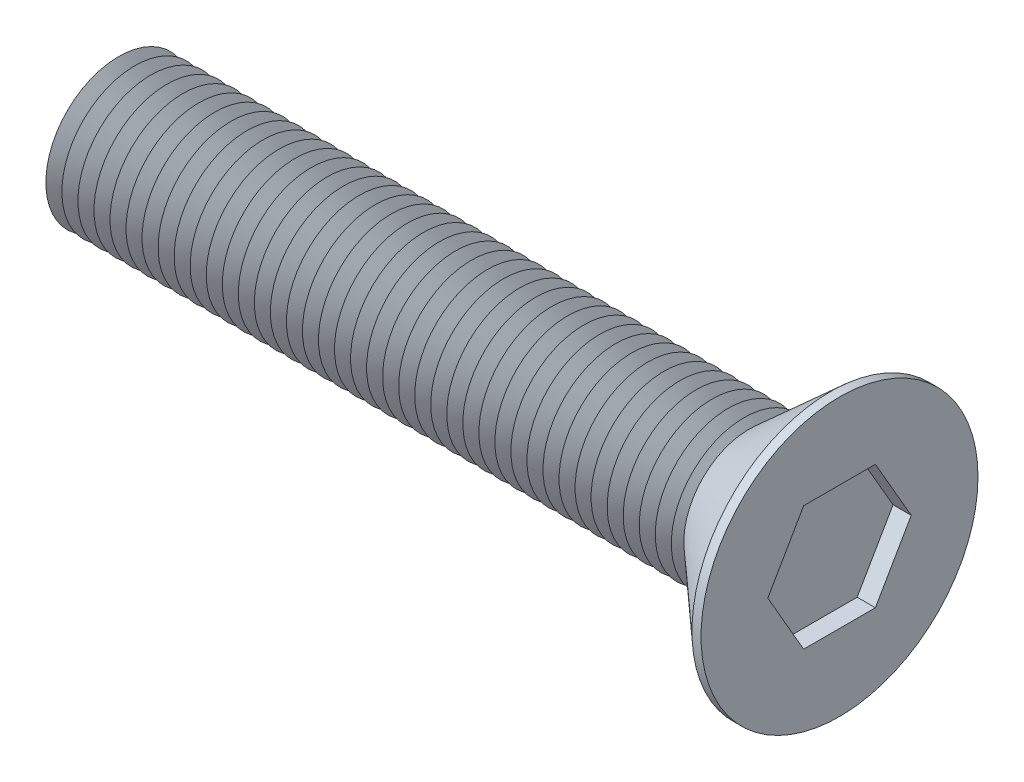
SolidWorks part; units mm, degrees
ref_plane "前视基准面" through (0, 0, 0) normal (0, 0, 1) x (1, 0, 0)
ref_plane "上视基准面" through (0, 0, 0) normal (0, 1, 0) x (1, 0, 0)
ref_plane "右视基准面" through (0, 0, 0) normal (1, 0, 0) x (0, 0, -1)
sketch "草图1" plane through (0, 0, 0) normal (0, 0, 1) x (1, 0, 0)
  line B0 (0, -3.3) -> (0, 0)
  line B1 (0.4401, -4) -> (0, -3.3)
  line B2 (40, 0) -> (0, 0)
  line B3 (40, -7.6) -> (40, 0)
  line B4 (39.5, -7.6) -> (40, -7.6)
  line B5 (39.5, -7.6) -> (35.0313, -3.5782)
  line B6 (0.4401, -4) -> (0.8802, -3.3)
  line B7 (1.3202, -4) -> (0.8802, -3.3)
  line B8 (1.3202, -4) -> (1.7603, -3.3)
  line B9 (2.2004, -4) -> (1.7603, -3.3)
  line B10 (2.2004, -4) -> (2.6405, -3.3)
  line B11 (3.0805, -4) -> (2.6405, -3.3)
  line B12 (3.0805, -4) -> (3.5206, -3.3)
  line B13 (3.9607, -4) -> (3.5206, -3.3)
  line B14 (3.9607, -4) -> (4.4008, -3.3)
  line B15 (4.8409, -4) -> (4.4008, -3.3)
  line B16 (4.8409, -4) -> (5.2809, -3.3)
  line B17 (5.721, -4) -> (5.2809, -3.3)
  line B18 (5.721, -4) -> (6.1611, -3.3)
  line B19 (6.6012, -4) -> (6.1611, -3.3)
  line B20 (6.6012, -4) -> (7.0413, -3.3)
  line B21 (7.4813, -4) -> (7.0413, -3.3)
  line B22 (7.4813, -4) -> (7.9214, -3.3)
  line B23 (8.3615, -4) -> (7.9214, -3.3)
  line B24 (8.3615, -4) -> (8.8016, -3.3)
  line B25 (9.2416, -4) -> (8.8016, -3.3)
  line B26 (9.2416, -4) -> (9.6817, -3.3)
  line B27 (10.1218, -4) -> (9.6817, -3.3)
  line B28 (10.1218, -4) -> (10.5619, -3.3)
  line B29 (11.002, -4) -> (10.5619, -3.3)
  line B30 (11.002, -4) -> (11.442, -3.3)
  line B31 (11.8821, -4) -> (11.442, -3.3)
  line B32 (11.8821, -4) -> (12.3222, -3.3)
  line B33 (12.7623, -4) -> (12.3222, -3.3)
  line B34 (12.7623, -4) -> (13.2023, -3.3)
  line B35 (13.6424, -4) -> (13.2023, -3.3)
  line B36 (13.6424, -4) -> (14.0825, -3.3)
  line B37 (14.5226, -4) -> (14.0825, -3.3)
  line B38 (14.5226, -4) -> (14.9627, -3.3)
  line B39 (15.4027, -4) -> (14.9627, -3.3)
  line B40 (15.4027, -4) -> (15.8428, -3.3)
  line B41 (16.2829, -4) -> (15.8428, -3.3)
  line B42 (16.2829, -4) -> (16.723, -3.3)
  line B43 (17.163, -4) -> (16.723, -3.3)
  line B44 (17.163, -4) -> (17.6031, -3.3)
  line B45 (18.0432, -4) -> (17.6031, -3.3)
  line B46 (18.0432, -4) -> (18.4833, -3.3)
  line B47 (18.9234, -4) -> (18.4833, -3.3)
  line B48 (18.9234, -4) -> (19.3634, -3.3)
  line B49 (19.8035, -4) -> (19.3634, -3.3)
  line B50 (19.8035, -4) -> (20.2436, -3.3)
  line B51 (20.6837, -4) -> (20.2436, -3.3)
  line B52 (20.6837, -4) -> (21.1238, -3.3)
  line B53 (21.5638, -4) -> (21.1238, -3.3)
  line B54 (21.5638, -4) -> (22.0039, -3.3)
  line B55 (22.444, -4) -> (22.0039, -3.3)
  line B56 (22.444, -4) -> (22.8841, -3.3)
  line B57 (23.3241, -4) -> (22.8841, -3.3)
  line B58 (23.3241, -4) -> (23.7642, -3.3)
  line B59 (24.2043, -4) -> (23.7642, -3.3)
  line B60 (24.2043, -4) -> (24.6444, -3.3)
  line B61 (25.0845, -4) -> (24.6444, -3.3)
  line B62 (25.0845, -4) -> (25.5245, -3.3)
  line B63 (25.9646, -4) -> (25.5245, -3.3)
  line B64 (25.9646, -4) -> (26.4047, -3.3)
  line B65 (26.8448, -4) -> (26.4047, -3.3)
  line B66 (26.8448, -4) -> (27.2848, -3.3)
  line B67 (27.7249, -4) -> (27.2848, -3.3)
  line B68 (27.7249, -4) -> (28.165, -3.3)
  line B69 (28.6051, -4) -> (28.165, -3.3)
  line B70 (28.6051, -4) -> (29.0452, -3.3)
  line B71 (29.4852, -4) -> (29.0452, -3.3)
  line B72 (29.4852, -4) -> (29.9253, -3.3)
  line B73 (30.3654, -4) -> (29.9253, -3.3)
  line B74 (30.3654, -4) -> (30.8055, -3.3)
  line B75 (31.2456, -4) -> (30.8055, -3.3)
  line B76 (31.2456, -4) -> (31.6856, -3.3)
  line B77 (32.1257, -4) -> (31.6856, -3.3)
  line B78 (32.1257, -4) -> (32.5658, -3.3)
  line B79 (33.0059, -4) -> (32.5658, -3.3)
  line B80 (33.0059, -4) -> (33.4459, -3.3)
  line B81 (33.886, -4) -> (33.4459, -3.3)
  line B82 (33.886, -4) -> (34.3261, -3.3)
  line B83 (34.7662, -4) -> (34.3261, -3.3)
  line B84 (34.7662, -4) -> (35.0313, -3.5782)
sketch_block_instance "A$C3B4A3A4C-1"
sketch_block "A$C3B4A3A4C"
revolve "旋转1" add sketch "草图1" angle 360 about L2
sketch "草图3" plane through (40, 0, 0) normal (1, 0, 0) x (0, 0, -1)
  line L1 (3.9366, 0) -> (1.9683, 3.4092)
  line L2 (1.9683, 3.4092) -> (-1.9683, 3.4092)
  line L3 (-1.9683, 3.4092) -> (-3.9366, 0)
  line L4 (-3.9366, 0) -> (-1.9683, -3.4092)
  line L5 (-1.9683, -3.4092) -> (1.9683, -3.4092)
  line L6 (1.9683, -3.4092) -> (3.9366, 0)
  circle A0 centre (0, 0) radius 3.4092 construction
extrude "切除-拉伸1" cut sketch "草图3" against normal blind 1
